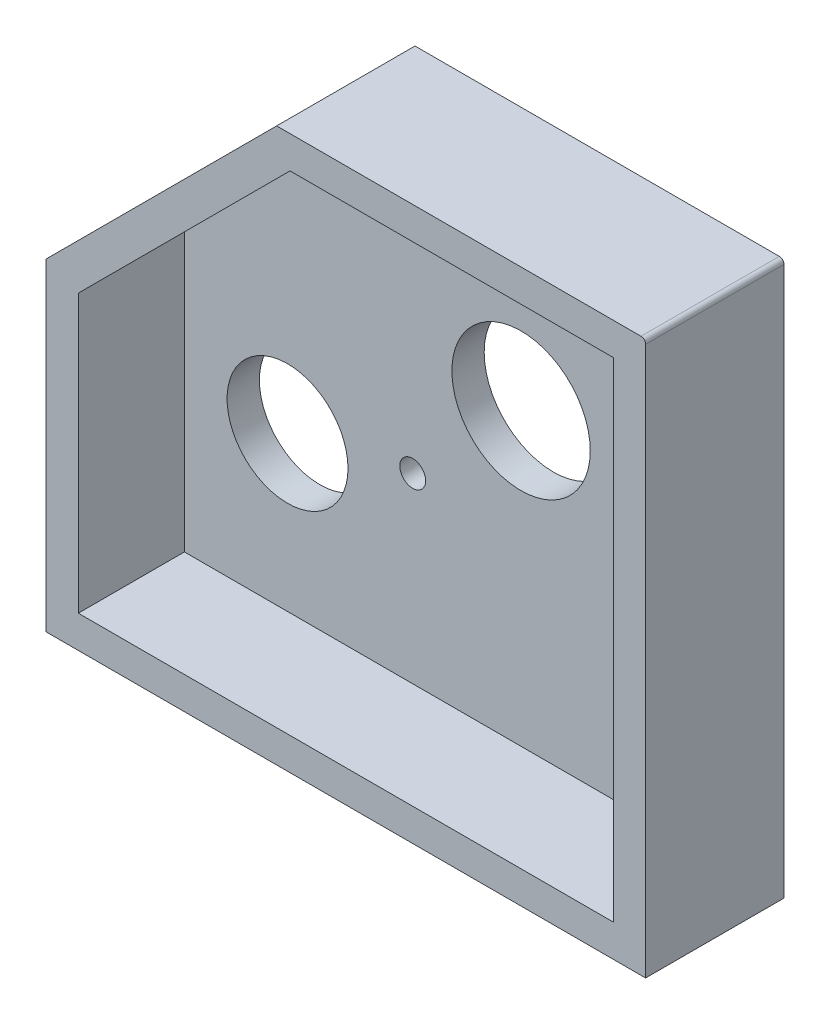
SolidWorks part; units mm, degrees
material "ABS"
ref_plane "Front Plane" through (0, 0, 0) normal (0, 0, 1) x (1, 0, 0)
ref_plane "Top Plane" through (0, 0, 0) normal (0, 1, 0) x (1, 0, 0)
ref_plane "Right Plane" through (0, 0, 0) normal (1, 0, 0) x (0, 0, -1)
sketch "Sketch1" plane through (0, 0, 0) normal (0, 0, 1) x (1, 0, 0)
  line L0 (-98.5887, 20.7376) -> (-48.5887, 70.7376)
  line L1 (-48.5887, 70.7376) -> (30.4113, 70.7376)
  line L2 (-98.5887, 20.7376) -> (-98.5887, -49.2624)
  line L3 (-98.5887, -49.2624) -> (31.4113, -49.2624)
  line L4 (31.4113, 69.7376) -> (31.4113, -49.2624)
  arc A0 (30.4113, 70.7376) -> (31.4113, 69.7376) centre (30.4113, 69.7376) cw
  point P0 (-98.6291, 70.596)
  point P6 (31.4113, 70.7376)
  point P7 (-98.5887, 70.7376)
  point P9 (-98.5887, 70.7376)
  point P10 (0, 0)
  point P11 (0, 0)
  point P12 (0, 0)
  point P13 (0, 0)
  point P14 (0, 0)
  point P15 (0, 0)
  point P16 (0, 0)
  point P17 (0, 0)
  point P18 (0, 0)
  point P19 (0, 0)
  point P20 (0, 0)
  point P21 (0, 0)
  point P22 (0, 0)
  point P23 (0, 0)
  point P24 (0, 0)
  point P25 (0, 0)
  point P26 (0, 0)
  point P27 (0, 0)
  point P28 (0, 0)
  point P29 (0, 0)
  point P30 (0, 0)
  dimension "D3" = 1
  dimension "D1" = 130
  dimension "D2" = 120
extrude "Boss-Extrude1" add sketch "Sketch1" along normal blind 30
shell "Shell1" thickness 7
sketch "Sketch2" plane through (0, 0, 7) normal (0, 0, 1) x (1, 0, 0)
  line L0 (30.4113, 70.7376) -> (-48.5887, 70.7376) construction
  line L1 (-98.5887, 20.7376) -> (-98.5887, -49.2624) construction
  circle A0 centre (-18.5887, 20.7376) radius 15
  dimension "D1" = 50
  dimension "D2" = 80
extrude "Cut-Extrude1" cut sketch "Sketch2" against normal blind 20
sketch "Sketch3" plane through (0, 0, 7) normal (0, 0, 1) x (1, 0, 0)
  circle A0 centre (-42.0887, 44.2376) radius 2.806
  circle A1 centre (-18.5887, 20.7376) radius 15 construction
  dimension "D1" = 23.5
  dimension "D2" = 23.5
extrude "Cut-Extrude2" cut sketch "Sketch3" against normal blind 20
pattern_linear "LPattern1" count 2 spacing 47 along (1, 0, 0) count 2 spacing 47 along (0, -1, 0) of "Cut-Extrude2"
sketch "Sketch4" plane through (0, 0, 7) normal (0, 0, 1) x (1, 0, 0)
  circle A0 centre (-69.2234, -8.8434) radius 13.1065
  point P2 (-69.2234, -8.8434)
extrude "Cut-Extrude3" cut sketch "Sketch4" against normal blind 20
